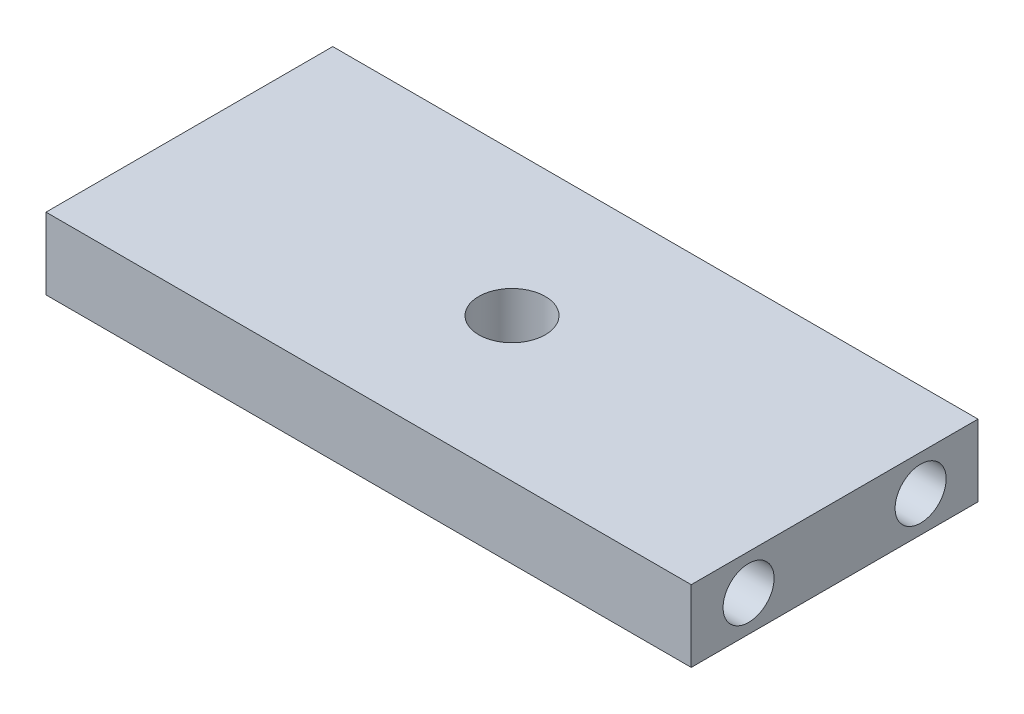
SolidWorks part; units mm, degrees
ref_plane "Front Plane" through (0, 0, 0) normal (0, 0, 1) x (1, 0, 0)
ref_plane "Top Plane" through (0, 0, 0) normal (0, 1, 0) x (1, 0, 0)
ref_plane "Right Plane" through (0, 0, 0) normal (1, 0, 0) x (0, 0, -1)
sketch "Sketch1" plane through (0, 0, 0) normal (1, 0, 0) x (0, 0, -1)
  line L1 (-6.35, -1.5875) -> (6.35, -1.5875)
  line L2 (-6.35, -1.5875) -> (-6.35, 1.5875)
  line L3 (-6.35, 1.5875) -> (6.35, 1.5875)
  line L4 (6.35, -1.5875) -> (6.35, 1.5875)
  line L5 (-6.35, -1.5875) -> (6.35, 1.5875) construction
  line L6 (-6.35, 1.5875) -> (6.35, -1.5875) construction
  point P0 (0, 0)
  dimension "D1" = 3.175
  dimension "D2" = 12.7
extrude "Boss-Extrude1" add sketch "Sketch1" along normal blind 28.575
hole_wizard "#4 Clearance Hole1" positions "Sketch3" profile "Sketch2" hole size "#4" standard "ANSI Inch"
sketch "Sketch3" plane through (0, 1.5875, 0) normal (0, 1, 0) x (1, 0, 0)
  line L0 (14.2875, 6.35) -> (14.2875, -6.35) construction
  line L1 (28.575, 6.35) -> (0, 6.35) construction
  line L2 (28.575, -6.35) -> (0, -6.35) construction
  point P0 (14.2875, 0)
sketch "Sketch2" plane through (14.2875, 1.5875, 0) normal (1, 0, 0) x (0, 0, 1)
  line L0 (0, 0) -> (0, 4.1872)
  line L1 (0, 4.1872) -> (1.4732, 3.302)
  line L2 (1.4732, 3.302) -> (1.4732, 0)
  line L5 (1.4732, 0) -> (0, 0)
  line L10 (0, 4.1872) -> (-1.4732, 3.302) construction
  line L11 (0, -6.35) -> (0, 107.95) construction
  dimension "Hole Dia." = 2.9464
  dimension "Hole Depth" = 3.302
  dimension "Drill Angle" = 118
hole_wizard "#4-40 Tapped Hole1" positions "Sketch7" profile "Sketch6" tap size "#4-40" standard "Progressive"
sketch "Sketch7" plane through (0, 0, 0) normal (-1, 0, 0) x (0, 0, 1)
  line L0 (-6.35, 0) -> (6.35, 0) construction
  line L1 (-6.35, -1.5875) -> (-6.35, 1.5875) construction
  line L2 (6.35, 1.5875) -> (6.35, -1.5875) construction
  line L3 (0, 1.5875) -> (0, -1.5875) construction
  line L4 (-6.35, 1.5875) -> (6.35, 1.5875) construction
  line L5 (6.35, -1.5875) -> (-6.35, -1.5875) construction
  point P9 (-3.81, 0)
  point P19 (3.81, 0)
  dimension "D1" = 3.81
sketch "Sketch6" plane through (0, 0, -3.81) normal (0, 1, 0) x (0, 0, 1)
  line L0 (0, 0) -> (0, 8.2992)
  line L1 (0, 8.2992) -> (1.1303, 7.62)
  line L2 (1.1303, 7.62) -> (1.1303, 0)
  line L5 (1.1303, 0) -> (0, 0)
  line L10 (0, 8.2992) -> (-1.1303, 7.62) construction
  line L11 (0, -6.35) -> (0, 107.95) construction
  dimension "Tap Drill Dia." = 2.2606
  dimension "Tap Drill Depth" = 7.62
  dimension "Drill Angle" = 118
cosmetic thread "Hole Thread1" parameters "D1"=5.588, "D2"=2.8448
cosmetic thread "Hole Thread2" parameters "D1"=5.588, "D2"=2.8448
hole_wizard "#4-40 Tapped Hole2" positions "Sketch9" profile "Sketch8" tap size "#4-40" standard "Progressive"
sketch "Sketch9" plane through (28.575, 0, 0) normal (1, 0, 0) x (0, 0, -1)
  line L0 (0, 1.5875) -> (0, -1.5875) construction
  line L1 (6.35, 1.5875) -> (-6.35, 1.5875) construction
  line L2 (-6.35, -1.5875) -> (6.35, -1.5875) construction
  point P0 (-3.81, 0)
  point P12 (3.81, 0)
  dimension "D1" = 3.81
sketch "Sketch8" plane through (28.575, 0, 3.81) normal (0, 1, 0) x (0, 0, -1)
  line L0 (0, 0) -> (0, 8.2992)
  line L1 (0, 8.2992) -> (1.1303, 7.62)
  line L2 (1.1303, 7.62) -> (1.1303, 0)
  line L5 (1.1303, 0) -> (0, 0)
  line L10 (0, 8.2992) -> (-1.1303, 7.62) construction
  line L11 (0, -6.35) -> (0, 107.95) construction
  dimension "Tap Drill Dia." = 2.2606
  dimension "Tap Drill Depth" = 7.62
  dimension "Drill Angle" = 118
cosmetic thread "Hole Thread3" parameters "D1"=5.588, "D2"=2.8448
cosmetic thread "Hole Thread4" parameters "D1"=5.588, "D2"=2.8448
